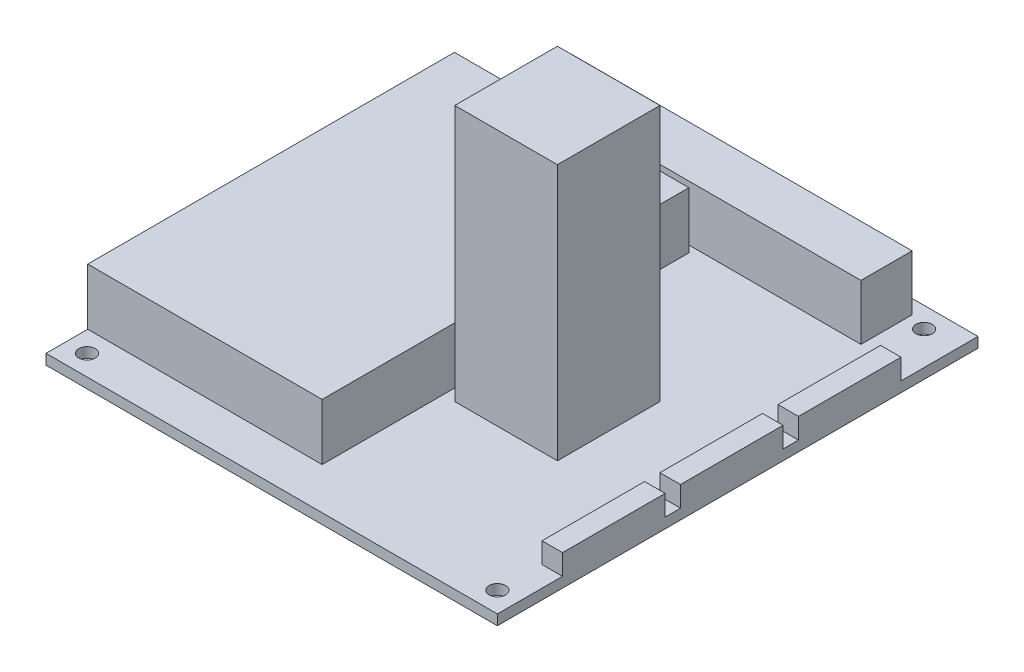
SolidWorks part; units mm, degrees
material "PBT General Purpose"
ref_plane "Front Plane" through (0, 0, 0) normal (0, 0, 1) x (1, 0, 0)
ref_plane "Top Plane" through (0, 0, 0) normal (0, 1, 0) x (1, 0, 0)
ref_plane "Right Plane" through (0, 0, 0) normal (1, 0, 0) x (0, 0, -1)
sketch "Sketch1" plane through (0, 0, 0) normal (0, 1, 0) x (1, 0, 0)
  line L0 (50, -50) -> (-50, -50) construction
  line L1 (50, -50) -> (50, 50) construction
  line L2 (50, 50) -> (-50, 50) construction
  line L3 (-50, -50) -> (-50, 50) construction
  line L4 (50, -50) -> (-50, 50) construction
  line L5 (50, 50) -> (-50, -50) construction
  line L6 (-50, 50) -> (-44, 50) construction
  line L7 (-50, 50) -> (-50, 44) construction
  line L8 (-50, 44) -> (-44, 44) construction
  line L9 (-44, 50) -> (-44, 44) construction
  line L10 (-50, -50) -> (-44, -50) construction
  line L11 (-50, -50) -> (-50, -44) construction
  line L12 (-50, -44) -> (-44, -44) construction
  line L13 (-44, -50) -> (-44, -44) construction
  line L14 (50, -50) -> (44, -50) construction
  line L15 (50, -50) -> (50, -44) construction
  line L16 (50, -44) -> (44, -44) construction
  line L17 (44, -50) -> (44, -44) construction
  line L18 (50, 50) -> (44, 50) construction
  line L19 (50, 50) -> (50, 44) construction
  line L20 (50, 44) -> (44, 44) construction
  line L21 (44, 50) -> (44, 44) construction
  line L22 (-32.625, 44.081) -> (33.923, 44.081) construction
  line L23 (-32.625, 44.081) -> (-32.625, 34.102) construction
  line L24 (-32.625, 34.102) -> (33.923, 34.102) construction
  line L25 (33.923, 44.081) -> (33.923, 34.102) construction
  line L26 (-50, 50) -> (-35, 50)
  line L27 (-50, 50) -> (-50, 48)
  line L28 (-50, 48) -> (-35, 48)
  line L29 (-35, 50) -> (-35, 48)
  line L30 (-50, 50) -> (-48, 50)
  line L31 (-50, 50) -> (-50, 35)
  line L32 (-50, 35) -> (-48, 35)
  line L33 (-48, 50) -> (-48, 35)
  line L34 (50, 50) -> (35, 50)
  line L35 (50, 50) -> (50, 48)
  line L36 (50, 48) -> (35, 48)
  line L37 (35, 50) -> (35, 48)
  line L38 (50, 50) -> (48, 50)
  line L39 (50, 50) -> (50, 35)
  line L40 (50, 35) -> (48, 35)
  line L41 (48, 50) -> (48, 35)
  line L42 (50, -50) -> (48, -50)
  line L43 (50, -50) -> (50, -35)
  line L44 (50, -35) -> (48, -35)
  line L45 (48, -50) -> (48, -35)
  line L46 (50, -50) -> (35, -50)
  line L47 (50, -50) -> (50, -48)
  line L48 (50, -48) -> (35, -48)
  line L49 (35, -50) -> (35, -48)
  line L50 (-50, -50) -> (-35, -50)
  line L51 (-50, -50) -> (-50, -48)
  line L52 (-50, -48) -> (-35, -48)
  line L53 (-35, -50) -> (-35, -48)
  line L54 (-50, -50) -> (-48, -50)
  line L55 (-50, -50) -> (-50, -35)
  line L56 (-50, -35) -> (-48, -35)
  line L57 (-48, -50) -> (-48, -35)
  circle A0 centre (-36.2, 42.85) radius 1.6
  circle A1 centre (37.5, 42.85) radius 1.6
  circle A2 centre (40, -42.85) radius 1.6
  circle A3 centre (-40, -42.85) radius 1.6
  point P0 (0, 0)
  point P5 (0, 0)
  point P6 (0, 0)
  dimension "D7" = 3.2
  dimension "D1" = 100
  dimension "D2" = 100
  dimension "D3" = 6
  dimension "D4" = 6
  dimension "D5" = 6
  dimension "D6" = 6
  dimension "D8" = 7.15
  dimension "D9" = 13.8
  dimension "D10" = 10
  dimension "D11" = 7.15
  dimension "D12" = 10
  dimension "D13" = 7.15
  dimension "D14" = 17.375
  dimension "D15" = 5.919
  dimension "D16" = 15.898
  dimension "D17" = 16.077
  dimension "D18" = 73.7
  dimension "D19" = 15
  dimension "D20" = 2
  dimension "D21" = 15
  dimension "D22" = 2
  dimension "D23" = 2
  dimension "D24" = 15
  dimension "D25" = 15
  dimension "D26" = 2
  dimension "D27" = 15
  dimension "D28" = 2
  dimension "D29" = 2
  dimension "D30" = 15
  dimension "D31" = 15
  dimension "D32" = 15
  dimension "D33" = 2
  dimension "D34" = 2
sketch "Sketch2" plane through (0, 0, 0) normal (0, 1, 0) x (1, 0, 0)
  line L0 (-32.625, 34.102) -> (33.923, 34.102) construction
  line L1 (33.923, 44.081) -> (33.923, 34.102) construction
  line L2 (-32.625, 44.081) -> (33.923, 44.081) construction
  line L3 (-32.625, 44.081) -> (-32.625, 34.102) construction
  line L4 (-32.625, 34.102) -> (33.923, 34.102)
  line L5 (33.923, 44.081) -> (33.923, 34.102)
  line L6 (-32.625, 44.081) -> (33.923, 44.081)
  line L7 (-32.625, 44.081) -> (-32.625, 34.102)
  line L9 (44, 46.85) -> (-44, 46.85) construction
  line L10 (44, 46.85) -> (44, -46.85) construction
  line L11 (44, -46.85) -> (-44, -46.85) construction
  line L12 (-44, 46.85) -> (-44, -46.85) construction
  line L13 (44, 46.85) -> (-44, -46.85) construction
  line L14 (44, -46.85) -> (-44, 46.85) construction
  line L15 (40, 31.85) -> (44, 31.85)
  line L16 (40, 31.85) -> (40, 11.85)
  line L17 (40, 11.85) -> (44, 11.85)
  line L18 (44, 31.85) -> (44, 11.85)
  line L26 (40, 8.85) -> (40, -11.15)
  line L27 (40, 8.85) -> (44, 8.85)
  line L28 (44, 8.85) -> (44, -11.15)
  line L29 (40, -11.15) -> (44, -11.15)
  line L30 (40, -14.15) -> (40, -34.15)
  line L31 (40, -14.15) -> (44, -14.15)
  line L32 (44, -14.15) -> (44, -34.15)
  line L33 (40, -34.15) -> (44, -34.15)
  line L35 (24, 4.85) -> (4, 4.85)
  line L36 (24, 4.85) -> (24, -15.15)
  line L37 (24, -15.15) -> (4, -15.15)
  line L38 (4, 4.85) -> (4, -15.15)
  line L39 (24, 4.85) -> (4, -15.15) construction
  line L40 (24, -15.15) -> (4, 4.85) construction
  line L41 (-44, 32.7817) -> (1.7, 32.7817)
  line L42 (-44, 32.7817) -> (-44, -38.7183)
  line L43 (-44, -38.7183) -> (1.7, -38.7183)
  line L44 (1.7, 32.7817) -> (1.7, -38.7183)
  circle A0 centre (40, -42.85) radius 1.6 construction
  circle A1 centre (-40, -42.85) radius 1.6 construction
  circle A2 centre (37.5, 42.85) radius 1.6 construction
  circle A3 centre (-36.2, 42.85) radius 1.6 construction
  circle A4 centre (40, -42.85) radius 1.6
  circle A5 centre (-40, -42.85) radius 1.6
  circle A6 centre (37.5, 42.85) radius 1.6
  circle A7 centre (-36.2, 42.85) radius 1.6
  point P15 (0, 0)
  point P23 (14, -5.15)
  dimension "D1" = 4
  dimension "D2" = 4
  dimension "D3" = 4
  dimension "D4" = 20
  dimension "D6" = 42
  dimension "D7" = 20
  dimension "D8" = 20
  dimension "D9" = 20
  dimension "D10" = 15
  dimension "D11" = 3
  dimension "D12" = 45.7
  dimension "D13" = 71.5
  dimension "D5" = 3
sketch "Sketch3" plane through (0, 0, 0) normal (0, 1, 0) x (1, 0, 0)
  line L0 (44, -46.85) -> (-44, -46.85) construction
  line L1 (44, 46.85) -> (44, -46.85) construction
  line L2 (-44, 46.85) -> (-44, -46.85) construction
  line L3 (44, 46.85) -> (-44, 46.85) construction
  line L4 (44, -46.85) -> (-44, -46.85)
  line L5 (44, 46.85) -> (44, -46.85)
  line L6 (-44, 46.85) -> (-44, -46.85)
  line L7 (44, 46.85) -> (-44, 46.85)
  circle A0 centre (-40, -42.85) radius 1.6 construction
  circle A1 centre (37.5, 42.85) radius 1.6 construction
  circle A2 centre (-36.2, 42.85) radius 1.6 construction
  circle A3 centre (-40, -42.85) radius 1.6
  circle A4 centre (37.5, 42.85) radius 1.6
  circle A5 centre (-36.2, 42.85) radius 1.6
  circle A6 centre (40, -42.85) radius 1.6 construction
  circle A7 centre (40, -42.85) radius 1.6
extrude "Boss-Extrude1" add sketch "Sketch3" along normal blind 2
sketch "Sketch4" plane through (0, 2, 0) normal (0, 1, 0) x (1, 0, 0)
  line L0 (-44, -38.7183) -> (1.7, -38.7183) construction
  line L1 (1.7, 32.7817) -> (1.7, -38.7183) construction
  line L2 (-44, 32.7817) -> (1.7, 32.7817) construction
  line L3 (-44, 32.7817) -> (-44, -38.7183) construction
  line L4 (-44, -38.7183) -> (1.7, -38.7183)
  line L5 (1.7, 32.7817) -> (1.7, -38.7183)
  line L6 (-44, 32.7817) -> (1.7, 32.7817)
  line L7 (-44, 32.7817) -> (-44, -38.7183)
extrude "Boss-Extrude2" add sketch "Sketch4" along normal blind 11
sketch "Sketch5" plane through (0, 2, 0) normal (0, 1, 0) x (1, 0, 0)
  line L0 (-32.625, 44.081) -> (33.923, 44.081) construction
  line L1 (33.923, 44.081) -> (33.923, 34.102) construction
  line L2 (-32.625, 34.102) -> (33.923, 34.102) construction
  line L3 (-32.625, 44.081) -> (-32.625, 34.102) construction
  line L4 (-32.625, 44.081) -> (33.923, 44.081)
  line L5 (33.923, 44.081) -> (33.923, 34.102)
  line L6 (-32.625, 34.102) -> (33.923, 34.102)
  line L7 (-32.625, 44.081) -> (-32.625, 34.102)
extrude "Boss-Extrude3" add sketch "Sketch5" along normal blind 10.8
sketch "Sketch6" plane through (0, 2, 0) normal (0, 1, 0) x (1, 0, 0)
  line L0 (24, -15.15) -> (4, -15.15) construction
  line L1 (4, 4.85) -> (4, -15.15) construction
  line L2 (24, 4.85) -> (4, 4.85) construction
  line L3 (24, 4.85) -> (24, -15.15) construction
  line L4 (24, -15.15) -> (4, -15.15)
  line L5 (4, 4.85) -> (4, -15.15)
  line L6 (24, 4.85) -> (4, 4.85)
  line L7 (24, 4.85) -> (24, -15.15)
extrude "Boss-Extrude4" add sketch "Sketch6" along normal blind 50
sketch "Sketch7" plane through (0, 2, 0) normal (0, 1, 0) x (1, 0, 0)
  line L0 (40, 31.85) -> (40, 11.85) construction
  line L1 (40, 11.85) -> (44, 11.85) construction
  line L2 (44, 31.85) -> (44, 11.85) construction
  line L3 (40, 31.85) -> (44, 31.85) construction
  line L4 (40, 8.85) -> (40, -11.15) construction
  line L5 (40, -11.15) -> (44, -11.15) construction
  line L6 (44, 8.85) -> (44, -11.15) construction
  line L7 (40, 8.85) -> (44, 8.85) construction
  line L8 (40, -14.15) -> (40, -34.15) construction
  line L9 (40, -34.15) -> (44, -34.15) construction
  line L10 (44, -14.15) -> (44, -34.15) construction
  line L11 (40, -14.15) -> (44, -14.15) construction
  line L12 (40, 31.85) -> (40, 11.85)
  line L13 (40, 11.85) -> (44, 11.85)
  line L14 (44, 31.85) -> (44, 11.85)
  line L15 (40, 31.85) -> (44, 31.85)
  line L16 (40, 8.85) -> (40, -11.15)
  line L17 (40, -11.15) -> (44, -11.15)
  line L18 (44, 8.85) -> (44, -11.15)
  line L19 (40, 8.85) -> (44, 8.85)
  line L20 (40, -14.15) -> (40, -34.15)
  line L21 (40, -34.15) -> (44, -34.15)
  line L22 (44, -14.15) -> (44, -34.15)
  line L23 (40, -14.15) -> (44, -14.15)
extrude "Boss-Extrude5" add sketch "Sketch7" along normal blind 4
sketch "Sketch8" plane through (0, 2, 0) normal (0, 1, 0) x (1, 0, 0)
  line L0 (-32.625, 44.081) -> (33.923, 44.081) construction
  line L1 (-31.672, 43.128) -> (-31.037, 43.128)
  line L2 (-31.672, 43.128) -> (-31.672, 42.493)
  line L3 (-31.672, 42.493) -> (-31.037, 42.493)
  line L4 (-31.037, 43.128) -> (-31.037, 42.493)
  line L5 (-32.625, 44.081) -> (-32.625, 34.102) construction
  line L6 (-29.132, 43.128) -> (-29.132, 42.493)
  line L7 (-29.132, 43.128) -> (-28.497, 43.128)
  line L8 (-29.132, 42.493) -> (-28.497, 42.493)
  line L9 (-28.497, 43.128) -> (-28.497, 42.493)
  line L10 (-26.592, 43.128) -> (-26.592, 42.493)
  line L11 (-26.592, 43.128) -> (-25.957, 43.128)
  line L12 (-26.592, 42.493) -> (-25.957, 42.493)
  line L13 (-25.957, 43.128) -> (-25.957, 42.493)
  line L14 (-24.052, 43.128) -> (-24.052, 42.493)
  line L15 (-24.052, 43.128) -> (-23.417, 43.128)
  line L16 (-24.052, 42.493) -> (-23.417, 42.493)
  line L17 (-23.417, 43.128) -> (-23.417, 42.493)
  line L18 (-21.512, 43.128) -> (-21.512, 42.493)
  line L19 (-21.512, 43.128) -> (-20.877, 43.128)
  line L20 (-21.512, 42.493) -> (-20.877, 42.493)
  line L21 (-20.877, 43.128) -> (-20.877, 42.493)
  line L22 (-18.972, 43.128) -> (-18.972, 42.493)
  line L23 (-18.972, 43.128) -> (-18.337, 43.128)
  line L24 (-18.972, 42.493) -> (-18.337, 42.493)
  line L25 (-18.337, 43.128) -> (-18.337, 42.493)
  line L26 (-16.432, 43.128) -> (-16.432, 42.493)
  line L27 (-16.432, 43.128) -> (-15.797, 43.128)
  line L28 (-16.432, 42.493) -> (-15.797, 42.493)
  line L29 (-15.797, 43.128) -> (-15.797, 42.493)
  line L30 (-13.892, 43.128) -> (-13.892, 42.493)
  line L31 (-13.892, 43.128) -> (-13.257, 43.128)
  line L32 (-13.892, 42.493) -> (-13.257, 42.493)
  line L33 (-13.257, 43.128) -> (-13.257, 42.493)
  line L34 (-11.352, 43.128) -> (-11.352, 42.493)
  line L35 (-11.352, 43.128) -> (-10.717, 43.128)
  line L36 (-11.352, 42.493) -> (-10.717, 42.493)
  line L37 (-10.717, 43.128) -> (-10.717, 42.493)
  line L38 (-8.812, 43.128) -> (-8.812, 42.493)
  line L39 (-8.812, 43.128) -> (-8.177, 43.128)
  line L40 (-8.812, 42.493) -> (-8.177, 42.493)
  line L41 (-8.177, 43.128) -> (-8.177, 42.493)
  line L42 (-6.272, 43.128) -> (-6.272, 42.493)
  line L43 (-6.272, 43.128) -> (-5.637, 43.128)
  line L44 (-6.272, 42.493) -> (-5.637, 42.493)
  line L45 (-5.637, 43.128) -> (-5.637, 42.493)
  line L46 (-3.732, 43.128) -> (-3.732, 42.493)
  line L47 (-3.732, 43.128) -> (-3.097, 43.128)
  line L48 (-3.732, 42.493) -> (-3.097, 42.493)
  line L49 (-3.097, 43.128) -> (-3.097, 42.493)
  line L50 (-1.192, 43.128) -> (-1.192, 42.493)
  line L51 (-1.192, 43.128) -> (-0.557, 43.128)
  line L52 (-1.192, 42.493) -> (-0.557, 42.493)
  line L53 (-0.557, 43.128) -> (-0.557, 42.493)
  line L54 (1.348, 43.128) -> (1.348, 42.493)
  line L55 (1.348, 43.128) -> (1.983, 43.128)
  line L56 (1.348, 42.493) -> (1.983, 42.493)
  line L57 (1.983, 43.128) -> (1.983, 42.493)
  line L58 (3.888, 43.128) -> (3.888, 42.493)
  line L59 (3.888, 43.128) -> (4.523, 43.128)
  line L60 (3.888, 42.493) -> (4.523, 42.493)
  line L61 (4.523, 43.128) -> (4.523, 42.493)
  line L62 (6.428, 43.128) -> (6.428, 42.493)
  line L63 (6.428, 43.128) -> (7.063, 43.128)
  line L64 (6.428, 42.493) -> (7.063, 42.493)
  line L65 (7.063, 43.128) -> (7.063, 42.493)
  line L66 (8.968, 43.128) -> (8.968, 42.493)
  line L67 (8.968, 43.128) -> (9.603, 43.128)
  line L68 (8.968, 42.493) -> (9.603, 42.493)
  line L69 (9.603, 43.128) -> (9.603, 42.493)
  line L70 (11.508, 43.128) -> (11.508, 42.493)
  line L71 (11.508, 43.128) -> (12.143, 43.128)
  line L72 (11.508, 42.493) -> (12.143, 42.493)
  line L73 (12.143, 43.128) -> (12.143, 42.493)
  line L74 (14.048, 43.128) -> (14.048, 42.493)
  line L75 (14.048, 43.128) -> (14.683, 43.128)
  line L76 (14.048, 42.493) -> (14.683, 42.493)
  line L77 (14.683, 43.128) -> (14.683, 42.493)
  line L78 (16.588, 43.128) -> (16.588, 42.493)
  line L79 (16.588, 43.128) -> (17.223, 43.128)
  line L80 (16.588, 42.493) -> (17.223, 42.493)
  line L81 (17.223, 43.128) -> (17.223, 42.493)
  line L82 (19.128, 43.128) -> (19.128, 42.493)
  line L83 (19.128, 43.128) -> (19.763, 43.128)
  line L84 (19.128, 42.493) -> (19.763, 42.493)
  line L85 (19.763, 43.128) -> (19.763, 42.493)
  line L86 (21.668, 43.128) -> (21.668, 42.493)
  line L87 (21.668, 43.128) -> (22.303, 43.128)
  line L88 (21.668, 42.493) -> (22.303, 42.493)
  line L89 (22.303, 43.128) -> (22.303, 42.493)
  line L90 (24.208, 43.128) -> (24.208, 42.493)
  line L91 (24.208, 43.128) -> (24.843, 43.128)
  line L92 (24.208, 42.493) -> (24.843, 42.493)
  line L93 (24.843, 43.128) -> (24.843, 42.493)
  line L94 (26.748, 43.128) -> (26.748, 42.493)
  line L95 (26.748, 43.128) -> (27.383, 43.128)
  line L96 (26.748, 42.493) -> (27.383, 42.493)
  line L97 (27.383, 43.128) -> (27.383, 42.493)
  line L98 (29.288, 43.128) -> (29.288, 42.493)
  line L99 (29.288, 43.128) -> (29.923, 43.128)
  line L100 (29.288, 42.493) -> (29.923, 42.493)
  line L101 (29.923, 43.128) -> (29.923, 42.493)
  line L102 (31.828, 43.128) -> (31.828, 42.493)
  line L103 (31.828, 43.128) -> (32.463, 43.128)
  line L104 (31.828, 42.493) -> (32.463, 42.493)
  line L105 (32.463, 43.128) -> (32.463, 42.493)
  line L106 (-29.132, 40.588) -> (-29.132, 39.953)
  line L107 (-29.132, 40.588) -> (-28.497, 40.588)
  line L108 (-29.132, 39.953) -> (-28.497, 39.953)
  line L109 (-28.497, 40.588) -> (-28.497, 39.953)
  line L110 (-26.592, 40.588) -> (-26.592, 39.953)
  line L111 (-26.592, 40.588) -> (-25.957, 40.588)
  line L112 (-26.592, 39.953) -> (-25.957, 39.953)
  line L113 (-25.957, 40.588) -> (-25.957, 39.953)
  line L114 (-24.052, 40.588) -> (-24.052, 39.953)
  line L115 (-24.052, 40.588) -> (-23.417, 40.588)
  line L116 (-24.052, 39.953) -> (-23.417, 39.953)
  line L117 (-23.417, 40.588) -> (-23.417, 39.953)
  line L118 (-21.512, 40.588) -> (-21.512, 39.953)
  line L119 (-21.512, 40.588) -> (-20.877, 40.588)
  line L120 (-21.512, 39.953) -> (-20.877, 39.953)
  line L121 (-20.877, 40.588) -> (-20.877, 39.953)
  line L122 (-18.972, 40.588) -> (-18.972, 39.953)
  line L123 (-18.972, 40.588) -> (-18.337, 40.588)
  line L124 (-18.972, 39.953) -> (-18.337, 39.953)
  line L125 (-18.337, 40.588) -> (-18.337, 39.953)
  line L126 (-16.432, 40.588) -> (-16.432, 39.953)
  line L127 (-16.432, 40.588) -> (-15.797, 40.588)
  line L128 (-16.432, 39.953) -> (-15.797, 39.953)
  line L129 (-15.797, 40.588) -> (-15.797, 39.953)
  line L130 (-13.892, 40.588) -> (-13.892, 39.953)
  line L131 (-13.892, 40.588) -> (-13.257, 40.588)
  line L132 (-13.892, 39.953) -> (-13.257, 39.953)
  line L133 (-13.257, 40.588) -> (-13.257, 39.953)
  line L134 (-11.352, 40.588) -> (-11.352, 39.953)
  line L135 (-11.352, 40.588) -> (-10.717, 40.588)
  line L136 (-11.352, 39.953) -> (-10.717, 39.953)
  line L137 (-10.717, 40.588) -> (-10.717, 39.953)
  line L138 (-8.812, 40.588) -> (-8.812, 39.953)
  line L139 (-8.812, 40.588) -> (-8.177, 40.588)
  line L140 (-8.812, 39.953) -> (-8.177, 39.953)
  line L141 (-8.177, 40.588) -> (-8.177, 39.953)
  line L142 (-6.272, 40.588) -> (-6.272, 39.953)
  line L143 (-6.272, 40.588) -> (-5.637, 40.588)
  line L144 (-6.272, 39.953) -> (-5.637, 39.953)
  line L145 (-5.637, 40.588) -> (-5.637, 39.953)
  line L146 (-3.732, 40.588) -> (-3.732, 39.953)
  line L147 (-3.732, 40.588) -> (-3.097, 40.588)
  line L148 (-3.732, 39.953) -> (-3.097, 39.953)
  line L149 (-3.097, 40.588) -> (-3.097, 39.953)
  line L150 (-1.192, 40.588) -> (-1.192, 39.953)
  line L151 (-1.192, 40.588) -> (-0.557, 40.588)
  line L152 (-1.192, 39.953) -> (-0.557, 39.953)
  line L153 (-0.557, 40.588) -> (-0.557, 39.953)
  line L154 (1.348, 40.588) -> (1.348, 39.953)
  line L155 (1.348, 40.588) -> (1.983, 40.588)
  line L156 (1.348, 39.953) -> (1.983, 39.953)
  line L157 (1.983, 40.588) -> (1.983, 39.953)
  line L158 (3.888, 40.588) -> (3.888, 39.953)
  line L159 (3.888, 40.588) -> (4.523, 40.588)
  line L160 (3.888, 39.953) -> (4.523, 39.953)
  line L161 (4.523, 40.588) -> (4.523, 39.953)
  line L162 (6.428, 40.588) -> (6.428, 39.953)
  line L163 (6.428, 40.588) -> (7.063, 40.588)
  line L164 (6.428, 39.953) -> (7.063, 39.953)
  line L165 (7.063, 40.588) -> (7.063, 39.953)
  line L166 (8.968, 40.588) -> (8.968, 39.953)
  line L167 (8.968, 40.588) -> (9.603, 40.588)
  line L168 (8.968, 39.953) -> (9.603, 39.953)
  line L169 (9.603, 40.588) -> (9.603, 39.953)
  line L170 (11.508, 40.588) -> (11.508, 39.953)
  line L171 (11.508, 40.588) -> (12.143, 40.588)
  line L172 (11.508, 39.953) -> (12.143, 39.953)
  line L173 (12.143, 40.588) -> (12.143, 39.953)
  line L174 (14.048, 40.588) -> (14.048, 39.953)
  line L175 (14.048, 40.588) -> (14.683, 40.588)
  line L176 (14.048, 39.953) -> (14.683, 39.953)
  line L177 (14.683, 40.588) -> (14.683, 39.953)
  line L178 (16.588, 40.588) -> (16.588, 39.953)
  line L179 (16.588, 40.588) -> (17.223, 40.588)
  line L180 (16.588, 39.953) -> (17.223, 39.953)
  line L181 (17.223, 40.588) -> (17.223, 39.953)
  line L182 (19.128, 40.588) -> (19.128, 39.953)
  line L183 (19.128, 40.588) -> (19.763, 40.588)
  line L184 (19.128, 39.953) -> (19.763, 39.953)
  line L185 (19.763, 40.588) -> (19.763, 39.953)
  line L186 (21.668, 40.588) -> (21.668, 39.953)
  line L187 (21.668, 40.588) -> (22.303, 40.588)
  line L188 (21.668, 39.953) -> (22.303, 39.953)
  line L189 (22.303, 40.588) -> (22.303, 39.953)
  line L190 (24.208, 40.588) -> (24.208, 39.953)
  line L191 (24.208, 40.588) -> (24.843, 40.588)
  line L192 (24.208, 39.953) -> (24.843, 39.953)
  line L193 (24.843, 40.588) -> (24.843, 39.953)
  line L194 (26.748, 40.588) -> (26.748, 39.953)
  line L195 (26.748, 40.588) -> (27.383, 40.588)
  line L196 (26.748, 39.953) -> (27.383, 39.953)
  line L197 (27.383, 40.588) -> (27.383, 39.953)
  line L198 (29.288, 40.588) -> (29.288, 39.953)
  line L199 (29.288, 40.588) -> (29.923, 40.588)
  line L200 (29.288, 39.953) -> (29.923, 39.953)
  line L201 (29.923, 40.588) -> (29.923, 39.953)
  line L202 (31.828, 40.588) -> (31.828, 39.953)
  line L203 (31.828, 40.588) -> (32.463, 40.588)
  line L204 (31.828, 39.953) -> (32.463, 39.953)
  line L205 (32.463, 40.588) -> (32.463, 39.953)
  line L206 (-29.132, 38.048) -> (-29.132, 37.413)
  line L207 (-29.132, 38.048) -> (-28.497, 38.048)
  line L208 (-29.132, 37.413) -> (-28.497, 37.413)
  line L209 (-28.497, 38.048) -> (-28.497, 37.413)
  line L210 (-26.592, 38.048) -> (-26.592, 37.413)
  line L211 (-26.592, 38.048) -> (-25.957, 38.048)
  line L212 (-26.592, 37.413) -> (-25.957, 37.413)
  line L213 (-25.957, 38.048) -> (-25.957, 37.413)
  line L214 (-24.052, 38.048) -> (-24.052, 37.413)
  line L215 (-24.052, 38.048) -> (-23.417, 38.048)
  line L216 (-24.052, 37.413) -> (-23.417, 37.413)
  line L217 (-23.417, 38.048) -> (-23.417, 37.413)
  line L218 (-21.512, 38.048) -> (-21.512, 37.413)
  line L219 (-21.512, 38.048) -> (-20.877, 38.048)
  line L220 (-21.512, 37.413) -> (-20.877, 37.413)
  line L221 (-20.877, 38.048) -> (-20.877, 37.413)
  line L222 (-18.972, 38.048) -> (-18.972, 37.413)
  line L223 (-18.972, 38.048) -> (-18.337, 38.048)
  line L224 (-18.972, 37.413) -> (-18.337, 37.413)
  line L225 (-18.337, 38.048) -> (-18.337, 37.413)
  line L226 (-16.432, 38.048) -> (-16.432, 37.413)
  line L227 (-16.432, 38.048) -> (-15.797, 38.048)
  line L228 (-16.432, 37.413) -> (-15.797, 37.413)
  line L229 (-15.797, 38.048) -> (-15.797, 37.413)
  line L230 (-13.892, 38.048) -> (-13.892, 37.413)
  line L231 (-13.892, 38.048) -> (-13.257, 38.048)
  line L232 (-13.892, 37.413) -> (-13.257, 37.413)
  line L233 (-13.257, 38.048) -> (-13.257, 37.413)
  line L234 (-11.352, 38.048) -> (-11.352, 37.413)
  line L235 (-11.352, 38.048) -> (-10.717, 38.048)
  line L236 (-11.352, 37.413) -> (-10.717, 37.413)
  line L237 (-10.717, 38.048) -> (-10.717, 37.413)
  line L238 (-8.812, 38.048) -> (-8.812, 37.413)
  line L239 (-8.812, 38.048) -> (-8.177, 38.048)
  line L240 (-8.812, 37.413) -> (-8.177, 37.413)
  line L241 (-8.177, 38.048) -> (-8.177, 37.413)
  line L242 (-6.272, 38.048) -> (-6.272, 37.413)
  line L243 (-6.272, 38.048) -> (-5.637, 38.048)
  line L244 (-6.272, 37.413) -> (-5.637, 37.413)
  line L245 (-5.637, 38.048) -> (-5.637, 37.413)
  line L246 (-3.732, 38.048) -> (-3.732, 37.413)
  line L247 (-3.732, 38.048) -> (-3.097, 38.048)
  line L248 (-3.732, 37.413) -> (-3.097, 37.413)
  line L249 (-3.097, 38.048) -> (-3.097, 37.413)
  line L250 (-1.192, 38.048) -> (-1.192, 37.413)
  line L251 (-1.192, 38.048) -> (-0.557, 38.048)
  line L252 (-1.192, 37.413) -> (-0.557, 37.413)
  line L253 (-0.557, 38.048) -> (-0.557, 37.413)
  line L254 (1.348, 38.048) -> (1.348, 37.413)
  line L255 (1.348, 38.048) -> (1.983, 38.048)
  line L256 (1.348, 37.413) -> (1.983, 37.413)
  line L257 (1.983, 38.048) -> (1.983, 37.413)
  line L258 (3.888, 38.048) -> (3.888, 37.413)
  line L259 (3.888, 38.048) -> (4.523, 38.048)
  line L260 (3.888, 37.413) -> (4.523, 37.413)
  line L261 (4.523, 38.048) -> (4.523, 37.413)
  line L262 (6.428, 38.048) -> (6.428, 37.413)
  line L263 (6.428, 38.048) -> (7.063, 38.048)
  line L264 (6.428, 37.413) -> (7.063, 37.413)
  line L265 (7.063, 38.048) -> (7.063, 37.413)
  line L266 (8.968, 38.048) -> (8.968, 37.413)
  line L267 (8.968, 38.048) -> (9.603, 38.048)
  line L268 (8.968, 37.413) -> (9.603, 37.413)
  line L269 (9.603, 38.048) -> (9.603, 37.413)
  line L270 (11.508, 38.048) -> (11.508, 37.413)
  line L271 (11.508, 38.048) -> (12.143, 38.048)
  line L272 (11.508, 37.413) -> (12.143, 37.413)
  line L273 (12.143, 38.048) -> (12.143, 37.413)
  line L274 (14.048, 38.048) -> (14.048, 37.413)
  line L275 (14.048, 38.048) -> (14.683, 38.048)
  line L276 (14.048, 37.413) -> (14.683, 37.413)
  line L277 (14.683, 38.048) -> (14.683, 37.413)
  line L278 (16.588, 38.048) -> (16.588, 37.413)
  line L279 (16.588, 38.048) -> (17.223, 38.048)
  line L280 (16.588, 37.413) -> (17.223, 37.413)
  line L281 (17.223, 38.048) -> (17.223, 37.413)
  line L282 (19.128, 38.048) -> (19.128, 37.413)
  line L283 (19.128, 38.048) -> (19.763, 38.048)
  line L284 (19.128, 37.413) -> (19.763, 37.413)
  line L285 (19.763, 38.048) -> (19.763, 37.413)
  line L286 (21.668, 38.048) -> (21.668, 37.413)
  line L287 (21.668, 38.048) -> (22.303, 38.048)
  line L288 (21.668, 37.413) -> (22.303, 37.413)
  line L289 (22.303, 38.048) -> (22.303, 37.413)
  line L290 (24.208, 38.048) -> (24.208, 37.413)
  line L291 (24.208, 38.048) -> (24.843, 38.048)
  line L292 (24.208, 37.413) -> (24.843, 37.413)
  line L293 (24.843, 38.048) -> (24.843, 37.413)
  line L294 (26.748, 38.048) -> (26.748, 37.413)
  line L295 (26.748, 38.048) -> (27.383, 38.048)
  line L296 (26.748, 37.413) -> (27.383, 37.413)
  line L297 (27.383, 38.048) -> (27.383, 37.413)
  line L298 (29.288, 38.048) -> (29.288, 37.413)
  line L299 (29.288, 38.048) -> (29.923, 38.048)
  line L300 (29.288, 37.413) -> (29.923, 37.413)
  line L301 (29.923, 38.048) -> (29.923, 37.413)
  line L302 (31.828, 38.048) -> (31.828, 37.413)
  line L303 (31.828, 38.048) -> (32.463, 38.048)
  line L304 (31.828, 37.413) -> (32.463, 37.413)
  line L305 (32.463, 38.048) -> (32.463, 37.413)
  line L306 (-29.132, 35.508) -> (-29.132, 34.873)
  line L307 (-29.132, 35.508) -> (-28.497, 35.508)
  line L308 (-29.132, 34.873) -> (-28.497, 34.873)
  line L309 (-28.497, 35.508) -> (-28.497, 34.873)
  line L310 (-26.592, 35.508) -> (-26.592, 34.873)
  line L311 (-26.592, 35.508) -> (-25.957, 35.508)
  line L312 (-26.592, 34.873) -> (-25.957, 34.873)
  line L313 (-25.957, 35.508) -> (-25.957, 34.873)
  line L314 (-24.052, 35.508) -> (-24.052, 34.873)
  line L315 (-24.052, 35.508) -> (-23.417, 35.508)
  line L316 (-24.052, 34.873) -> (-23.417, 34.873)
  line L317 (-23.417, 35.508) -> (-23.417, 34.873)
  line L318 (-21.512, 35.508) -> (-21.512, 34.873)
  line L319 (-21.512, 35.508) -> (-20.877, 35.508)
  line L320 (-21.512, 34.873) -> (-20.877, 34.873)
  line L321 (-20.877, 35.508) -> (-20.877, 34.873)
  line L322 (-18.972, 35.508) -> (-18.972, 34.873)
  line L323 (-18.972, 35.508) -> (-18.337, 35.508)
  line L324 (-18.972, 34.873) -> (-18.337, 34.873)
  line L325 (-18.337, 35.508) -> (-18.337, 34.873)
  line L326 (-16.432, 35.508) -> (-16.432, 34.873)
  line L327 (-16.432, 35.508) -> (-15.797, 35.508)
  line L328 (-16.432, 34.873) -> (-15.797, 34.873)
  line L329 (-15.797, 35.508) -> (-15.797, 34.873)
  line L330 (-13.892, 35.508) -> (-13.892, 34.873)
  line L331 (-13.892, 35.508) -> (-13.257, 35.508)
  line L332 (-13.892, 34.873) -> (-13.257, 34.873)
  line L333 (-13.257, 35.508) -> (-13.257, 34.873)
  line L334 (-11.352, 35.508) -> (-11.352, 34.873)
  line L335 (-11.352, 35.508) -> (-10.717, 35.508)
  line L336 (-11.352, 34.873) -> (-10.717, 34.873)
  line L337 (-10.717, 35.508) -> (-10.717, 34.873)
  line L338 (-8.812, 35.508) -> (-8.812, 34.873)
  line L339 (-8.812, 35.508) -> (-8.177, 35.508)
  line L340 (-8.812, 34.873) -> (-8.177, 34.873)
  line L341 (-8.177, 35.508) -> (-8.177, 34.873)
  line L342 (-6.272, 35.508) -> (-6.272, 34.873)
  line L343 (-6.272, 35.508) -> (-5.637, 35.508)
  line L344 (-6.272, 34.873) -> (-5.637, 34.873)
  line L345 (-5.637, 35.508) -> (-5.637, 34.873)
  line L346 (-3.732, 35.508) -> (-3.732, 34.873)
  line L347 (-3.732, 35.508) -> (-3.097, 35.508)
  line L348 (-3.732, 34.873) -> (-3.097, 34.873)
  line L349 (-3.097, 35.508) -> (-3.097, 34.873)
  line L350 (-1.192, 35.508) -> (-1.192, 34.873)
  line L351 (-1.192, 35.508) -> (-0.557, 35.508)
  line L352 (-1.192, 34.873) -> (-0.557, 34.873)
  line L353 (-0.557, 35.508) -> (-0.557, 34.873)
  line L354 (1.348, 35.508) -> (1.348, 34.873)
  line L355 (1.348, 35.508) -> (1.983, 35.508)
  line L356 (1.348, 34.873) -> (1.983, 34.873)
  line L357 (1.983, 35.508) -> (1.983, 34.873)
  line L358 (3.888, 35.508) -> (3.888, 34.873)
  line L359 (3.888, 35.508) -> (4.523, 35.508)
  line L360 (3.888, 34.873) -> (4.523, 34.873)
  line L361 (4.523, 35.508) -> (4.523, 34.873)
  line L362 (6.428, 35.508) -> (6.428, 34.873)
  line L363 (6.428, 35.508) -> (7.063, 35.508)
  line L364 (6.428, 34.873) -> (7.063, 34.873)
  line L365 (7.063, 35.508) -> (7.063, 34.873)
  line L366 (8.968, 35.508) -> (8.968, 34.873)
  line L367 (8.968, 35.508) -> (9.603, 35.508)
  line L368 (8.968, 34.873) -> (9.603, 34.873)
  line L369 (9.603, 35.508) -> (9.603, 34.873)
  line L370 (11.508, 35.508) -> (11.508, 34.873)
  line L371 (11.508, 35.508) -> (12.143, 35.508)
  line L372 (11.508, 34.873) -> (12.143, 34.873)
  line L373 (12.143, 35.508) -> (12.143, 34.873)
  line L374 (14.048, 35.508) -> (14.048, 34.873)
  line L375 (14.048, 35.508) -> (14.683, 35.508)
  line L376 (14.048, 34.873) -> (14.683, 34.873)
  line L377 (14.683, 35.508) -> (14.683, 34.873)
  line L378 (16.588, 35.508) -> (16.588, 34.873)
  line L379 (16.588, 35.508) -> (17.223, 35.508)
  line L380 (16.588, 34.873) -> (17.223, 34.873)
  line L381 (17.223, 35.508) -> (17.223, 34.873)
  line L382 (19.128, 35.508) -> (19.128, 34.873)
  line L383 (19.128, 35.508) -> (19.763, 35.508)
  line L384 (19.128, 34.873) -> (19.763, 34.873)
  line L385 (19.763, 35.508) -> (19.763, 34.873)
  line L386 (21.668, 35.508) -> (21.668, 34.873)
  line L387 (21.668, 35.508) -> (22.303, 35.508)
  line L388 (21.668, 34.873) -> (22.303, 34.873)
  line L389 (22.303, 35.508) -> (22.303, 34.873)
  line L390 (24.208, 35.508) -> (24.208, 34.873)
  line L391 (24.208, 35.508) -> (24.843, 35.508)
  line L392 (24.208, 34.873) -> (24.843, 34.873)
  line L393 (24.843, 35.508) -> (24.843, 34.873)
  line L394 (26.748, 35.508) -> (26.748, 34.873)
  line L395 (26.748, 35.508) -> (27.383, 35.508)
  line L396 (26.748, 34.873) -> (27.383, 34.873)
  line L397 (27.383, 35.508) -> (27.383, 34.873)
  line L398 (29.288, 35.508) -> (29.288, 34.873)
  line L399 (29.288, 35.508) -> (29.923, 35.508)
  line L400 (29.288, 34.873) -> (29.923, 34.873)
  line L401 (29.923, 35.508) -> (29.923, 34.873)
  line L402 (31.828, 35.508) -> (31.828, 34.873)
  line L403 (31.828, 35.508) -> (32.463, 35.508)
  line L404 (31.828, 34.873) -> (32.463, 34.873)
  line L405 (32.463, 35.508) -> (32.463, 34.873)
  line L406 (-31.672, 40.588) -> (-31.672, 39.953)
  line L407 (-31.672, 40.588) -> (-31.037, 40.588)
  line L408 (-31.672, 39.953) -> (-31.037, 39.953)
  line L409 (-31.037, 40.588) -> (-31.037, 39.953)
  line L410 (-31.672, 38.048) -> (-31.672, 37.413)
  line L411 (-31.672, 38.048) -> (-31.037, 38.048)
  line L412 (-31.672, 37.413) -> (-31.037, 37.413)
  line L413 (-31.037, 38.048) -> (-31.037, 37.413)
  line L414 (-31.672, 35.508) -> (-31.672, 34.873)
  line L415 (-31.672, 35.508) -> (-31.037, 35.508)
  line L416 (-31.672, 34.873) -> (-31.037, 34.873)
  line L417 (-31.037, 35.508) -> (-31.037, 34.873)
  dimension "D1" = 0.635
  dimension "D2" = 0.635
  dimension "D3" = 0.953
  dimension "D4" = 0.953
  dimension "D5" = 26
  dimension "D6" = 4
extrude "Boss-Extrude6" add sketch "Sketch8" against normal blind 12
